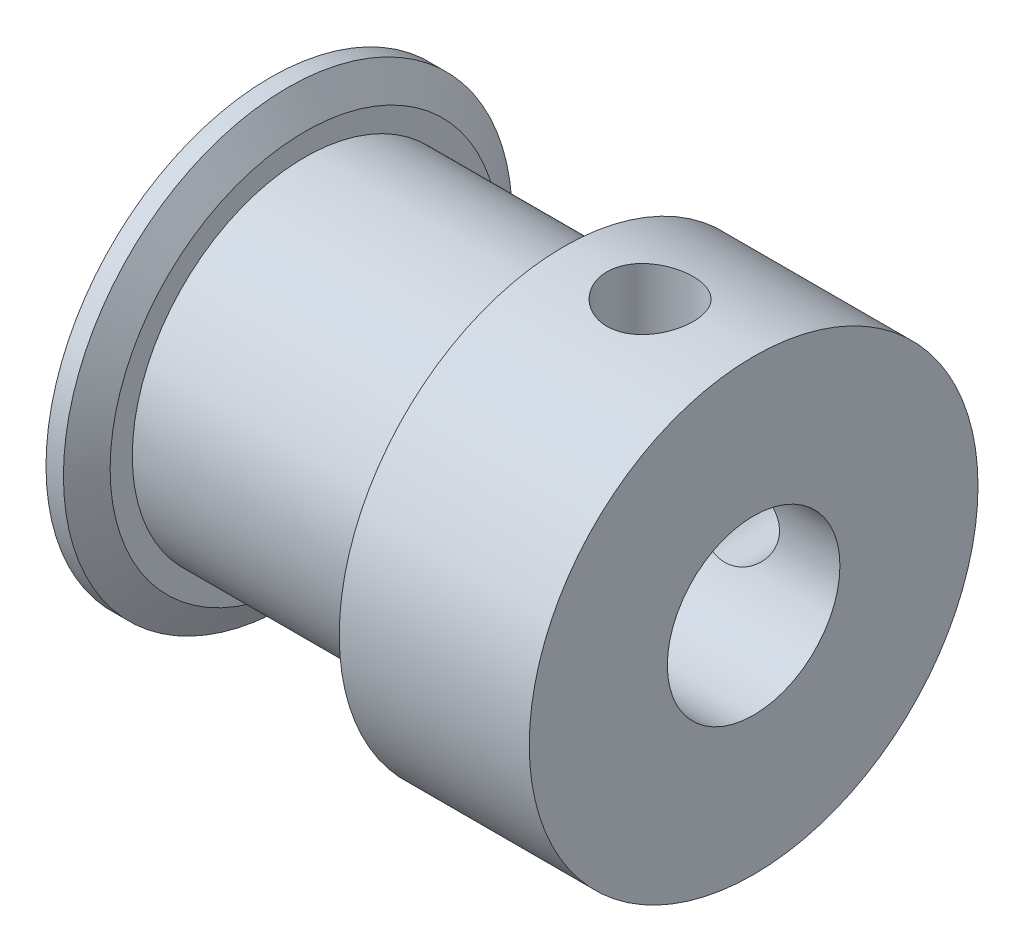
SolidWorks part; units mm, degrees
material "6063-O"
ref_plane "前视基准面" through (0, 0, 0) normal (0, 0, 1) x (1, 0, 0)
ref_plane "上视基准面" through (0, 0, 0) normal (0, 1, 0) x (1, 0, 0)
ref_plane "右视基准面" through (0, 0, 0) normal (1, 0, 0) x (0, 0, -1)
sketch "草图1" plane through (0, 0, 0) normal (0, 1, 0) x (1, 0, 0)
  line L0 (-10.7933, 0) -> (30.8031, 0) construction
  line L1 (0, 2.5) -> (0, 6.5) construction
  line L2 (0, 6.5) -> (0.5047, 6.5) construction
  line L3 (14, 6.5) -> (14, 2.5)
  line L4 (0, 2.5) -> (14, 2.5)
  line L7 (0, 6.5) -> (0.5047, 6.5)
  line L8 (0.5047, 6.5) -> (1, 5.6421)
  line L9 (1, 5) -> (8, 5)
  line L10 (1, 5.6421) -> (1, 5)
  line L11 (8, 5) -> (8, 5.6421)
  line L12 (8, 5.6421) -> (8.4953, 6.5)
  line L13 (8.4953, 6.5) -> (14, 6.5)
  line L15 (0, 6.5) -> (0, 2.5)
  dimension "D1" = 14
  dimension "D2" = 6.5
  dimension "D3" = 5
  dimension "D4" = 7
  dimension "D5" = 10
  dimension "D6" = 1
  dimension "D7" = 6
  dimension "D8" = 30
  dimension "D9" = 30
revolve "旋转1" add sketch "草图1" angle 360 about L0
ref_plane "基准面1" through (0, 6.5, 0) normal (0, 1, 0) x (1, 0, 0)
hole_wizard "M3 螺纹孔1" positions "草图3" profile "草图4" tap size "M3" standard "GB"
sketch "草图3" plane through (0, 6.5, 0) normal (0, 1, 0) x (1, 0, 0)
  line L0 (11, 7.9572) -> (11, -6.5617) construction
  line L2 (14, -6.5) -> (14, 6.5) construction
  point P0 (11, 0)
  dimension "D1" = 3
sketch "草图4" plane through (11, 6.5, 0) normal (1, 0, 0) x (0, 0, 1)
  line L0 (0, 0) -> (0, 13)
  line L1 (0, 13) -> (1.25, 13)
  line L2 (1.25, 13) -> (1.25, 0)
  line L5 (1.25, 0) -> (0, 0)
  line L11 (0, -6.35) -> (0, 107.95) construction
  dimension "通孔螺纹孔钻头直径" = 2.5
  dimension "通孔螺纹孔钻头深度" = 13
cosmetic thread "孔螺蚊线1" parameters "D2"=3
pattern_circular "阵列(圆周)1" count 2 over 90 about axis through (-10.7933, 0, 0) along (-1, 0, 0) of "M3 螺纹孔1"
